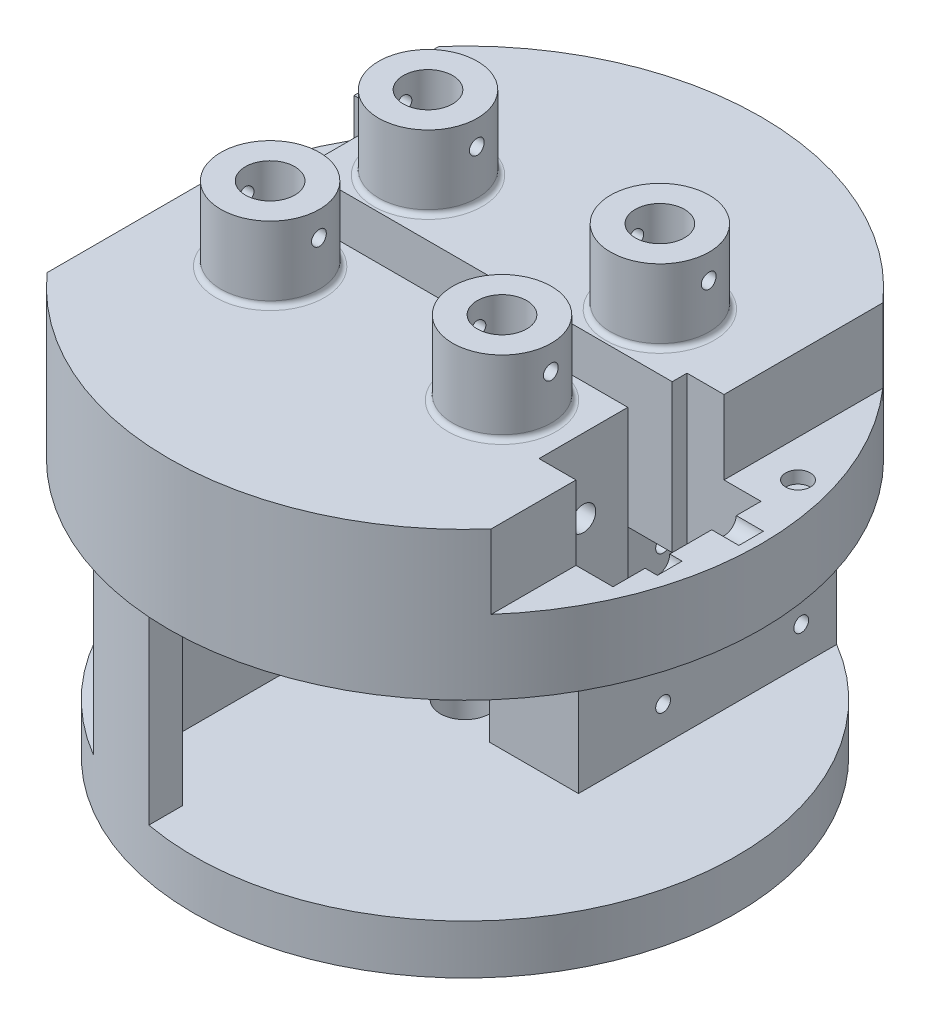
SolidWorks part; units mm, degrees
ref_plane "Front Plane" through (0, 0, 0) normal (0, 0, 1) x (1, 0, 0)
ref_plane "Top Plane" through (0, 0, 0) normal (0, 1, 0) x (1, 0, 0)
ref_plane "Right Plane" through (0, 0, 0) normal (1, 0, 0) x (0, 0, -1)
sketch "Sketch1" plane through (0, 0, 0) normal (0, 1, 0) x (1, 0, 0)
  circle A0 centre (0, 0) radius 55
  dimension "D1" = 110
extrude "Boss-Extrude1" add sketch "Sketch1" along normal blind 10
sketch "Sketch5" plane through (0, 10, 0) normal (0, 1, 0) x (1, 0, 0)
  line L0 (-73.7107, 0) -> (83.6973, 0) construction
  line L1 (0, -69.1137) -> (0, 62.4559) construction
  line L2 (0, 0) -> (20, 0) construction
  line L3 (0, 0) -> (-20, 0) construction
  line L4 (15, -47.3) -> (15, -5)
  line L5 (-15, 47.3) -> (23, 47.3)
  line L6 (-15, 47.3) -> (-15, 5)
  line L7 (-15, 5) -> (23, 5)
  line L8 (23, 47.3) -> (23, 5)
  line L9 (-15, 47.3) -> (23, 5) construction
  line L10 (-15, 5) -> (23, 47.3) construction
  line L11 (15, -47.3) -> (-23, -47.3)
  line L12 (-23, -47.3) -> (-23, -5)
  line L13 (15, -5) -> (-23, -5)
  line L15 (10, 0) -> (28, 0)
  line L16 (28, 53.066) -> (28, 0)
  line L20 (-28, -53.066) -> (-28, 0)
  line L22 (10, 59.1608) -> (10, 47.3)
  line L24 (10, 5) -> (10, 0)
  line L26 (-10, 0) -> (-10, -5)
  line L27 (-10, -47.3) -> (-10, -59.1608)
  line L28 (-10, 0) -> (-28, 0)
  line L29 (-20, 52.3) -> (28, 52.3) construction
  line L30 (-20, 52.3) -> (-20, 0) construction
  line L31 (28, 52.3) -> (28, 0) construction
  line L32 (20, -52.3) -> (20, 0) construction
  line L33 (20, -52.3) -> (-28, -52.3) construction
  line L34 (-28, -52.3) -> (-28, 0) construction
  line L35 (-20, 0) -> (28, 0) construction
  line L37 (20, 0) -> (-28, 0) construction
  line L38 (-10, 0) -> (5, 0)
  line L39 (-10, 0) -> (-10, -5)
  line L40 (-10, -5) -> (5, -5)
  line L41 (5, 0) -> (5, -5)
  line L42 (-5, 5) -> (10, 5)
  line L43 (-5, 5) -> (-5, 0)
  line L44 (-5, 0) -> (10, 0)
  line L45 (10, 5) -> (10, 0)
  circle A0 centre (0, 0) radius 60
  point P7 (4, 26.15)
  point P19 (0, 0)
  dimension "D10" = 120
  dimension "D1" = 20
  dimension "D2" = 20
  dimension "D4" = 42.3
  dimension "D5" = 5
  dimension "D6" = 5
  dimension "D7" = 38
  dimension "D11" = 20
  dimension "D12" = 10
  dimension "D9" = 10
  dimension "D13" = 5
  dimension "D8" = 5
  dimension "D3" = 2
extrude "Boss-Extrude5" add sketch "Sketch5" along normal blind 42.3
sketch "Sketch6" plane through (28, 0, 0) normal (1, 0, 0) x (0, 0, -1)
  line L6 (26.15, 52.3) -> (26.15, 10) construction
  line L11 (5, 31.15) -> (47.3, 31.15) construction
  line L18 (12.15, 45.15) -> (40.15, 45.15) construction
  line L20 (5, 10) -> (47.3, 10)
  line L21 (5, 52.3) -> (5, 10)
  line L22 (47.3, 52.3) -> (5, 52.3)
  line L23 (47.3, 10) -> (47.3, 52.3)
  line L24 (5, 10) -> (47.3, 10)
  line L25 (5, 52.3) -> (5, 10)
  line L26 (47.3, 52.3) -> (5, 52.3)
  line L27 (47.3, 10) -> (47.3, 52.3)
  line L28 (12.15, 45.15) -> (12.15, 17.15) construction
  line L29 (12.15, 17.15) -> (40.15, 17.15) construction
  line L30 (40.15, 45.15) -> (40.15, 17.15) construction
  line L31 (12.15, 45.15) -> (40.15, 17.15) construction
  line L32 (12.15, 17.15) -> (40.15, 45.15) construction
  circle A4 centre (12.15, 45.15) radius 1.5
  circle A5 centre (40.15, 45.15) radius 1.5
  circle A6 centre (40.15, 17.15) radius 1.5
  circle A7 centre (12.15, 17.15) radius 1.5
  point P10 (26.15, 31.15)
  dimension "D1" = 0
  dimension "D2" = 3
  dimension "D3" = 28
  dimension "D4" = 28
extrude "Cut-Extrude1" cut sketch "Sketch6" against normal through all contours A4 | A7 | A6 | A5
pattern_circular "CirPattern1" count 2 over 360 about axis through (0, 10, 0) along (0, 1, 0) of "Cut-Extrude1"
sketch "Sketch8" plane through (0, 10, 0) normal (0, 1, 0) x (1, 0, 0)
  line L0 (10, 47.3) -> (23, 47.3) construction
  line L1 (23, 5) -> (-15, 5)
  line L2 (23, 5) -> (23, 47.3)
  line L3 (23, 47.3) -> (-15, 47.3)
  line L4 (-15, 5) -> (-15, 47.3)
  line L5 (-10, -47.3) -> (-23, -47.3) construction
  line L6 (-23, -5) -> (15, -5)
  line L7 (-23, -5) -> (-23, -47.3)
  line L8 (-23, -47.3) -> (15, -47.3)
  line L9 (15, -5) -> (15, -47.3)
  line L10 (-15, 26.15) -> (-39, 26.15) construction
  line L11 (15, -26.15) -> (39, -26.15) construction
  dimension "D1" = 38
  dimension "D2" = 38
  dimension "D3" = 24
  dimension "D4" = 24
sketch "Sketch3" plane through (0, 52.3, 0) normal (0, 1, 0) x (1, 0, 0)
  circle A11 centre (0, 0) radius 60
  dimension "D1" = 120
extrude "Boss-Extrude4" add sketch "Sketch3" along normal blind 30
sketch "Sketch4" plane through (0, 82.3, 0) normal (0, 1, 0) x (1, 0, 0)
  line L1 (-23.5, 16) -> (23.5, 16) construction
  line L2 (-23.5, 16) -> (-23.5, -16) construction
  line L3 (-23.5, -16) -> (23.5, -16) construction
  line L4 (23.5, 16) -> (23.5, -16) construction
  line L5 (-23.5, 16) -> (23.5, -16) construction
  line L6 (-23.5, -16) -> (23.5, 16) construction
  circle A0 centre (-23.5, 16) radius 5
  circle A1 centre (23.5, 16) radius 5
  circle A2 centre (23.5, -16) radius 5
  circle A3 centre (-23.5, -16) radius 5
  circle A4 centre (-23.5, 16) radius 10
  circle A5 centre (23.5, 16) radius 10
  circle A6 centre (23.5, -16) radius 10
  circle A7 centre (-23.5, -16) radius 10
  point P0 (0, 0)
  dimension "D3" = 10
  dimension "D1" = 47
  dimension "D2" = 32
  dimension "D4" = 5
extrude "Boss-Extrude6" add sketch "Sketch4" along normal blind 15
fillet "Fillet1" radius 1 4 edges at (23.5, 82.3, -6) (-23.5, 82.3, -6) (23.5, 82.3, 26) (-23.5, 82.3, 26)
sketch "Sketch7" plane through (0, 0, 0) normal (1, 0, 0) x (0, 0, -1)
  line L0 (0, 0) -> (0, 82.3) construction
  line L1 (60, 82.3) -> (-60, 82.3) construction
  line L2 (0, 82.3) -> (0, 92.3) construction
  line L3 (0, 92.3) -> (16, 92.3) construction
  line L4 (0, 92.3) -> (-16, 92.3) construction
  circle A0 centre (16, 92.3) radius 1.5
  circle A1 centre (-16, 92.3) radius 1.5
  dimension "Set screw OD" = 3
  dimension "D1" = 10
  dimension "D2" = 16
extrude "Cut-Extrude2" cut sketch "Sketch7" along normal through all both and the other way through all
sketch "Sketch9" plane through (0, 82.3, 0) normal (0, 1, 0) x (1, 0, 0)
  line L0 (-60, 0) -> (60, 0) construction
  line L1 (0, 60) -> (0, -60) construction
  line L3 (-45, 4.5) -> (45, 4.5)
  line L4 (-45, 4.5) -> (-45, -4.5)
  line L5 (-45, -4.5) -> (45, -4.5)
  line L6 (45, 4.5) -> (45, -4.5)
  line L7 (-45, 4.5) -> (45, -4.5) construction
  line L8 (-45, -4.5) -> (45, 4.5) construction
  line L9 (-52.5, 7.5) -> (-37.5, 7.5)
  line L10 (-52.5, 7.5) -> (-52.5, -7.5)
  line L11 (-52.5, -7.5) -> (-37.5, -7.5)
  line L12 (-37.5, 7.5) -> (-37.5, -7.5)
  line L13 (-52.5, 7.5) -> (-37.5, -7.5) construction
  line L14 (-52.5, -7.5) -> (-37.5, 7.5) construction
  line L15 (37.5, 7.5) -> (52.5, 7.5)
  line L16 (37.5, 7.5) -> (37.5, -7.5)
  line L17 (37.5, -7.5) -> (52.5, -7.5)
  line L18 (52.5, 7.5) -> (52.5, -7.5)
  line L19 (37.5, 7.5) -> (52.5, -7.5) construction
  line L20 (37.5, -7.5) -> (52.5, 7.5) construction
  circle A0 centre (0, 0) radius 60 construction
  point P8 (0, 0)
  point P13 (-45, 0)
  point P18 (45, 0)
  dimension "D1" = 90
  dimension "D2" = 9
  dimension "D3" = 15
  dimension "D4" = 45
extrude "Cut-Extrude6" cut sketch "Sketch9" against normal up to surface (30 mm away) contours L12 L9 L10 L11 L5 L4 L3 | L16 L3 L12 L5 | L12 L3 L4 L5 | L3 L16 L5 L6 | L18 L15 L16 L3 L6 L5 L17 up to face at (0, 52.3, 60)
sketch "Sketch10" plane through (10, 0, 0) normal (-1, 0, 0) x (0, 0, 1)
  line L0 (-2.25, 52.3) -> (-2.25, 31.15) construction
  line L1 (-4.5, 52.3) -> (0, 52.3) construction
  circle A0 centre (-2.25, 31.15) radius 1
  dimension "Gt2 belt ID" = 2
  dimension "D1" = 21.15
sketch "Sketch11" plane through (0, 0, 0) normal (0, 0, -1) x (-1, 0, 0)
  line L1 (10, 52.3) -> (28, 52.3)
  line L2 (10, 52.3) -> (10, 10)
  line L3 (10, 10) -> (28, 10)
  line L4 (28, 52.3) -> (28, 10)
extrude "Boss-Extrude7" add sketch "Sketch11" along normal blind 5
sketch "Sketch12" plane through (-28, 0, 0) normal (-1, 0, 0) x (0, 0, 1)
  line L0 (-5, 52.3) -> (-5, 10) construction
  line L1 (-5, 52.3) -> (-5, 10)
sketch "Sketch14" plane through (0, 0, 0) normal (0, 0, 1) x (1, 0, 0)
  line L4 (10, 10) -> (28, 10)
  line L5 (28, 10) -> (28, 52.3)
  line L6 (28, 52.3) -> (10, 52.3)
  line L7 (10, 52.3) -> (10, 10)
  line L8 (10, 10) -> (28, 10)
  line L9 (28, 10) -> (28, 52.3)
  line L10 (28, 52.3) -> (10, 52.3)
  line L11 (10, 52.3) -> (10, 10)
  dimension "D1" = 0
extrude "Boss-Extrude8" add sketch "Sketch14" along normal blind 5
sketch "Sketch16" plane through (0, 82.3, 0) normal (0, 1, 0) x (1, 0, 0)
  line L0 (-37.5, -4.5) -> (-37.5, -7.5) construction
  line L1 (-52.5, 7.5) -> (-37.5, 7.5)
  line L2 (-52.5, 7.5) -> (-52.5, -7.5)
  line L3 (-52.5, -7.5) -> (-37.5, -7.5)
  line L4 (-37.5, 7.5) -> (-37.5, -7.5)
  line L5 (-52.5, -7.5) -> (-37.5, -7.5) construction
  line L7 (37.5, 7.5) -> (52.5, 7.5)
  line L8 (37.5, 7.5) -> (37.5, -7.5)
  line L9 (37.5, -7.5) -> (52.5, -7.5)
  line L10 (52.5, 7.5) -> (52.5, -7.5)
sketch "Sketch18" plane through (0, 52.3, 0) normal (0, 1, 0) x (1, 0, 0)
  line L4 (-10, -4.5) -> (-10, 4.5)
  line L5 (-10, 4.5) -> (-28, 4.5)
  line L6 (-28, 4.5) -> (-28, -4.5)
  line L7 (-28, -4.5) -> (-10, -4.5)
  line L8 (-10, -4.5) -> (-10, 4.5)
  line L9 (-10, 4.5) -> (-28, 4.5)
  line L10 (-28, 4.5) -> (-28, -4.5)
  line L11 (-28, -4.5) -> (-10, -4.5)
  line L12 (10, 4.5) -> (10, -4.5)
  line L13 (10, -4.5) -> (28, -4.5)
  line L14 (28, -4.5) -> (28, 4.5)
  line L15 (28, 4.5) -> (10, 4.5)
  line L16 (10, 4.5) -> (10, -4.5)
  line L17 (10, -4.5) -> (28, -4.5)
  line L18 (28, -4.5) -> (28, 4.5)
  line L19 (28, 4.5) -> (10, 4.5)
  dimension "D1" = 0
  dimension "D2" = 0
extrude "Boss-Extrude9" add sketch "Sketch18" along normal blind 15
sketch "Sketch19" plane through (-28, 0, 0) normal (-1, 0, 0) x (0, 0, 1)
  circle A0 centre (0, 67.5) radius 2.5
  dimension "D2" = 5
  dimension "D1" = 67.5
extrude "Cut-Extrude7" cut sketch "Sketch19" against normal blind 5 and the other way blind 30
mirror "Mirror1" about plane through (0, 0, 0) normal (1, 0, 0) of "Cut-Extrude7"
sketch "Sketch20" plane through (0, 0, 0) normal (1, 0, 0) x (0, 0, -1)
  line L0 (0, 0) -> (-50, 0) construction
  line L1 (-55, 0) -> (55, 0) construction
  circle A0 centre (-50, 0) radius 2.5
  dimension "Bearing Ball OD" = 5
  dimension "bearing ball track radius" = 50
sketch "Sketch21" plane through (0, 0, 0) normal (0, -1, 0) x (1, 0, 0)
  circle A0 centre (0, 0) radius 50
  dimension "Bearing Ball track Diameter" = 100
sweep "Cut-Sweep1" cut profiles "Sketch20" path "Sketch21"
sketch "Sketch22" plane through (0, 82.3, 0) normal (0, 1, 0) x (1, 0, 0)
  line L0 (-37.5, 7.5) -> (-37.5, -7.5) construction
  line L1 (-52.5, 7.5) -> (-37.5, 7.5)
  line L2 (-52.5, 7.5) -> (-52.5, 22.5)
  line L3 (-52.5, 22.5) -> (-37.5, 22.5)
  line L4 (-37.5, 7.5) -> (-37.5, 22.5)
  line L5 (52.5, 7.5) -> (52.5, -7.5) construction
  line L6 (37.5, -7.5) -> (52.5, -7.5)
  line L7 (37.5, -7.5) -> (37.5, -22.5)
  line L8 (37.5, -22.5) -> (52.5, -22.5)
  line L9 (52.5, -7.5) -> (52.5, -22.5)
  dimension "D1" = 15
  dimension "D2" = 15
extrude "Cut-Extrude8" cut sketch "Sketch22" against normal up to next
sketch "Sketch24" plane through (-37.5, 0, 0) normal (-1, 0, 0) x (0, 0, 1)
  line L0 (-13.5, 82.3) -> (-13.5, 52.3) construction
  line L1 (-22.5, 67.3) -> (-4.5, 67.3) construction
  line L4 (-4.5, 52.3) -> (-4.5, 82.3)
  line L5 (-4.5, 82.3) -> (-22.5, 82.3)
  line L6 (-22.5, 82.3) -> (-22.5, 52.3)
  line L7 (-22.5, 52.3) -> (-4.5, 52.3)
  line L8 (-4.5, 52.3) -> (-4.5, 82.3) construction
  line L9 (-4.5, 82.3) -> (-22.5, 82.3) construction
  line L10 (-22.5, 82.3) -> (-22.5, 52.3) construction
  line L11 (-22.5, 52.3) -> (-4.5, 52.3) construction
  circle A0 centre (-13.5, 67.3) radius 2.5
  dimension "D2" = 5
  dimension "D1" = 0
extrude "Cut-Extrude9" cut sketch "Sketch24" along normal blind 17.5 and the other way blind 5
sketch "Sketch25" plane through (37.5, 0, 0) normal (1, 0, 0) x (0, 0, -1)
  line L0 (-13.5, 82.3) -> (-13.5, 52.3) construction
  line L1 (-22.5, 67.3) -> (-4.5, 67.3) construction
  line L4 (-22.5, 52.3) -> (-4.5, 52.3)
  line L5 (-4.5, 52.3) -> (-4.5, 82.3)
  line L6 (-4.5, 82.3) -> (-22.5, 82.3)
  line L7 (-22.5, 82.3) -> (-22.5, 52.3)
  line L8 (-22.5, 52.3) -> (-4.5, 52.3) construction
  line L9 (-4.5, 52.3) -> (-4.5, 82.3) construction
  line L10 (-4.5, 82.3) -> (-22.5, 82.3) construction
  line L11 (-22.5, 82.3) -> (-22.5, 52.3) construction
  circle A0 centre (-13.5, 67.3) radius 2.5
  dimension "D2" = 5
  dimension "D1" = 0
extrude "Cut-Extrude10" cut sketch "Sketch25" along normal blind 17.5 and the other way blind 5
sketch "Sketch26" plane through (0, 82.3, 0) normal (0, 1, 0) x (1, 0, 0)
  line L0 (45, 7.5) -> (45, 39.6863)
  line L1 (-52.5, 22.5) -> (-45, 22.5)
  line L2 (-52.5, 22.5) -> (-52.5, -7.5)
  line L3 (-52.5, -7.5) -> (-45, -7.5)
  line L5 (45, 7.5) -> (52.5, 7.5)
  line L7 (45, -22.5) -> (52.5, -22.5)
  line L8 (52.5, 7.5) -> (52.5, -22.5)
  line L9 (45, -22.5) -> (45, -39.6863)
  line L10 (-45, -7.5) -> (-45, -39.6863)
  line L11 (-45, 22.5) -> (-45, 39.6863)
  circle A0 centre (0, 0) radius 60 construction
  arc A1 (-45, 39.6863) -> (-45, -39.6863) centre (0, 0) ccw
  arc A2 (45, -39.6863) -> (45, 39.6863) centre (0, 0) ccw
extrude "Cut-Extrude11" cut sketch "Sketch26" against normal blind 15
sketch "Sketch27" plane through (0, 67.3, 0) normal (0, 1, 0) x (1, 0, 0)
  line L0 (52.5, 7.5) -> (52.5, 15) construction
  line L1 (-52.5, -7.5) -> (-52.5, -15) construction
  circle A0 centre (-52.5, -15) radius 2.5
  circle A1 centre (52.5, 15) radius 2.5
  dimension "D2" = 5
  dimension "D1" = 7.5
extrude "Cut-Extrude12" cut sketch "Sketch27" against normal blind 2.5
sketch "Sketch28" plane through (0, 0, 0) normal (0, -1, 0) x (1, 0, 0)
  circle A0 centre (0, 0) radius 5
  dimension "Center Bolt OD" = 10
extrude "Cut-Extrude13" cut sketch "Sketch28" against normal up to next
